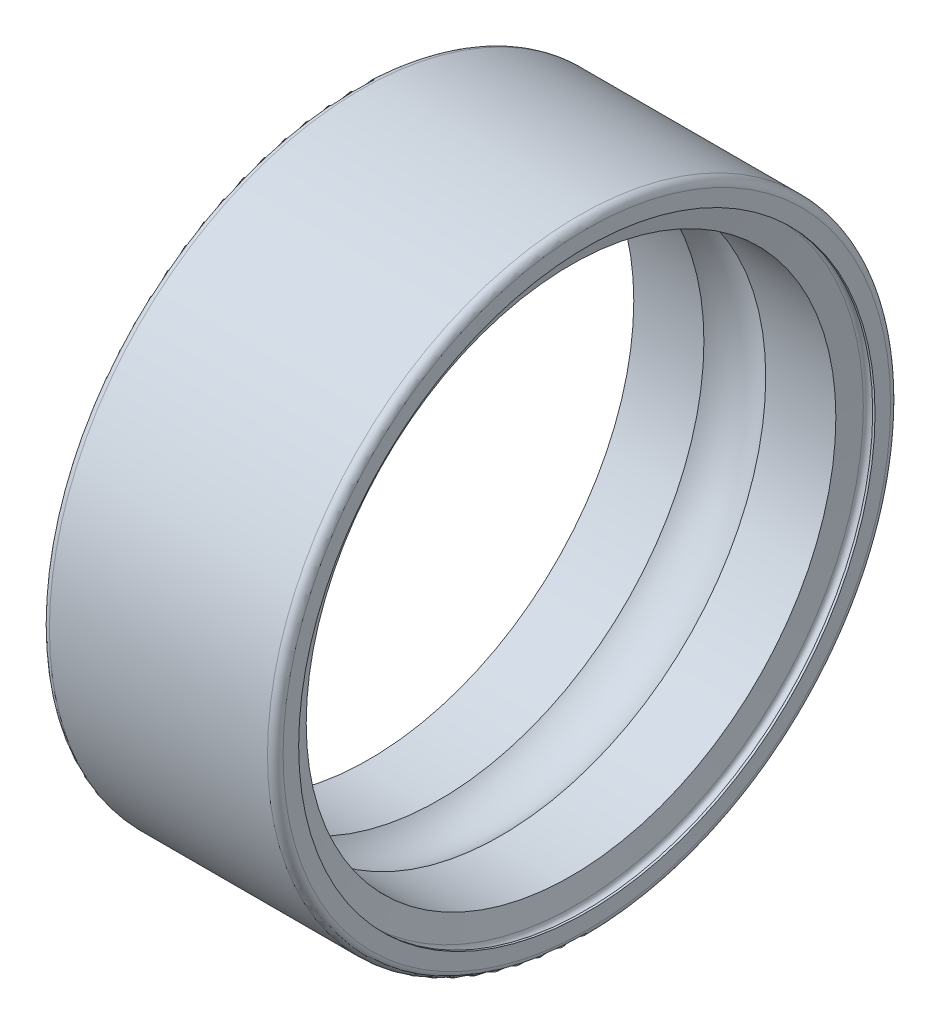
SolidWorks part; units mm, degrees
ref_plane "Ebene vorne" through (0, 0, 0) normal (0, 0, 1) x (1, 0, 0)
ref_plane "Ebene oben" through (0, 0, 0) normal (0, 1, 0) x (1, 0, 0)
ref_plane "Ebene rechts" through (0, 0, 0) normal (1, 0, 0) x (0, 0, -1)
ref_plane "Plane1" through (0, 0, 0) normal (0, 0, 1) x (1, 0, 0)
sketch "Sketch1" plane through (0, 0, 0) normal (0, 0, 1) x (1, 0, 0)
  line L0 (0, 3.9) -> (0, 3.7)
  line L1 (0, 3.7) -> (0.03, 3.7)
  line L2 (0.15, 3.7) -> (0.2029, 3.4)
  line L3 (0.2029, 3.4) -> (1.1031, 3.4)
  line L4 (1.8969, 3.4) -> (2.7971, 3.4)
  line L5 (2.7971, 3.4) -> (2.85, 3.7)
  line L6 (2.97, 3.7) -> (3, 3.7)
  line L7 (3, 3.7) -> (3, 3.9)
  line L8 (2.9, 4) -> (0.1, 4)
  line L9 (50, 0) -> (-50, 0) construction
  arc A0 (0.03, 3.7) -> (0.15, 3.7) centre (0.09, 3.7) cw
  arc A1 (1.1031, 3.4) -> (1.8969, 3.4) centre (1.5, 2.95) cw
  arc A2 (2.85, 3.7) -> (2.97, 3.7) centre (2.91, 3.7) cw
  arc A3 (3, 3.9) -> (2.9, 4) centre (2.9, 3.9) ccw
  arc A4 (0.1, 4) -> (0, 3.9) centre (0.1, 3.9) ccw
revolve "Revolve1" add sketch "Sketch1" angle 360 about L9
